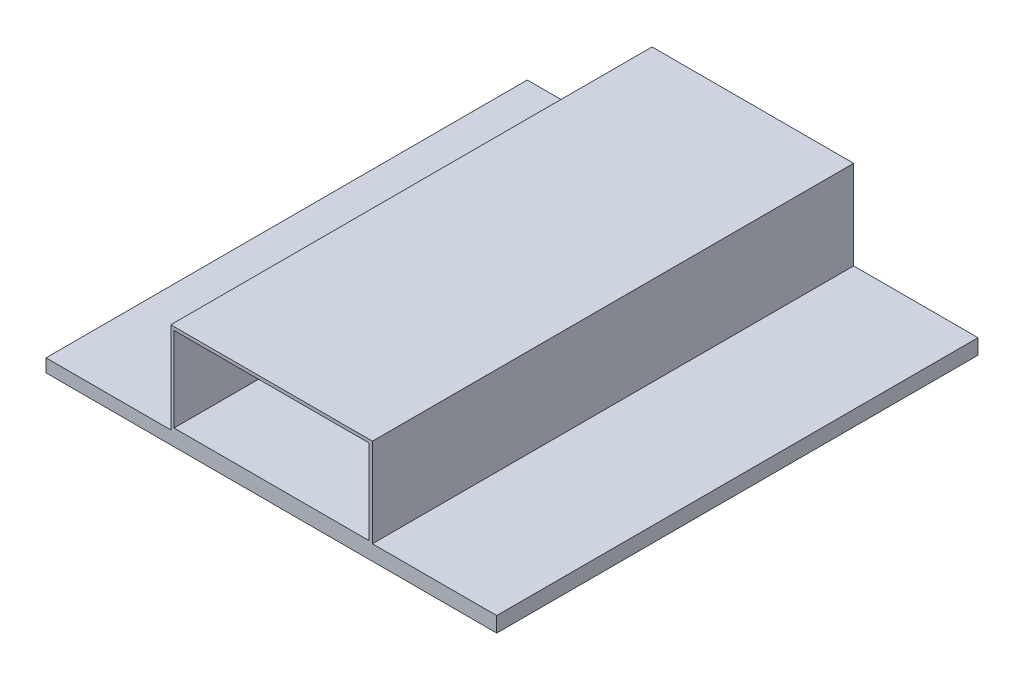
SolidWorks part; units mm, degrees
ref_plane "Alzado" through (0, 0, 0) normal (0, 0, 1) x (1, 0, 0)
ref_plane "Planta" through (0, 0, 0) normal (0, 1, 0) x (1, 0, 0)
ref_plane "Vista lateral" through (0, 0, 0) normal (1, 0, 0) x (0, 0, -1)
sketch "Croquis1" plane through (0, 0, 0) normal (0, 0, 1) x (1, 0, 0)
  line L7 (-35, -6.5) -> (-35, -8.5)
  line L8 (-35, -8.5) -> (34.3038, -8.5)
  line L9 (34.3038, -8.5) -> (34.3038, -6.1628)
  line L11 (-15.8119, -6.5) -> (-15.8119, 7.5)
  line L12 (-15.8119, 7.5) -> (15.1881, 7.5)
  line L13 (15.1881, 7.5) -> (15.1881, -6.1628)
  line L14 (15.1881, -6.1628) -> (34.3038, -6.1628)
  line L15 (-35, -6.5) -> (-15.8119, -6.5)
  point P0 (0, 0)
  point P1 (0, 0)
  point P12 (0, 0)
  point P15 (-15.7282, 7.1628)
  dimension "D1" = 14
  dimension "D2" = 31
  dimension "D3" = 2
extrude "Saliente-Extruir1" add sketch "Croquis1" along normal blind 74
sketch "Croquis2" plane through (0, 0, 74) normal (0, 0, 1) x (1, 0, 0)
  line L1 (-15.3119, -6) -> (14.6881, -6)
  line L2 (-15.3119, -6) -> (-15.3119, 7)
  line L3 (-15.3119, 7) -> (14.6881, 7)
  line L4 (14.6881, -6) -> (14.6881, 7)
  line L7 (15.1881, 7.5) -> (-15.8119, 7.5) construction
  point P0 (0, 0)
  point P5 (-0.3119, -6.4467)
  point P10 (0, 0)
  point P11 (0, 0)
  point P12 (0, 0)
  point P13 (0, 0)
  dimension "D1" = 30
  dimension "D2" = 13
  dimension "D3" = 0.5
extrude "Cortar-Extruir1" cut sketch "Croquis2" against normal blind 72
